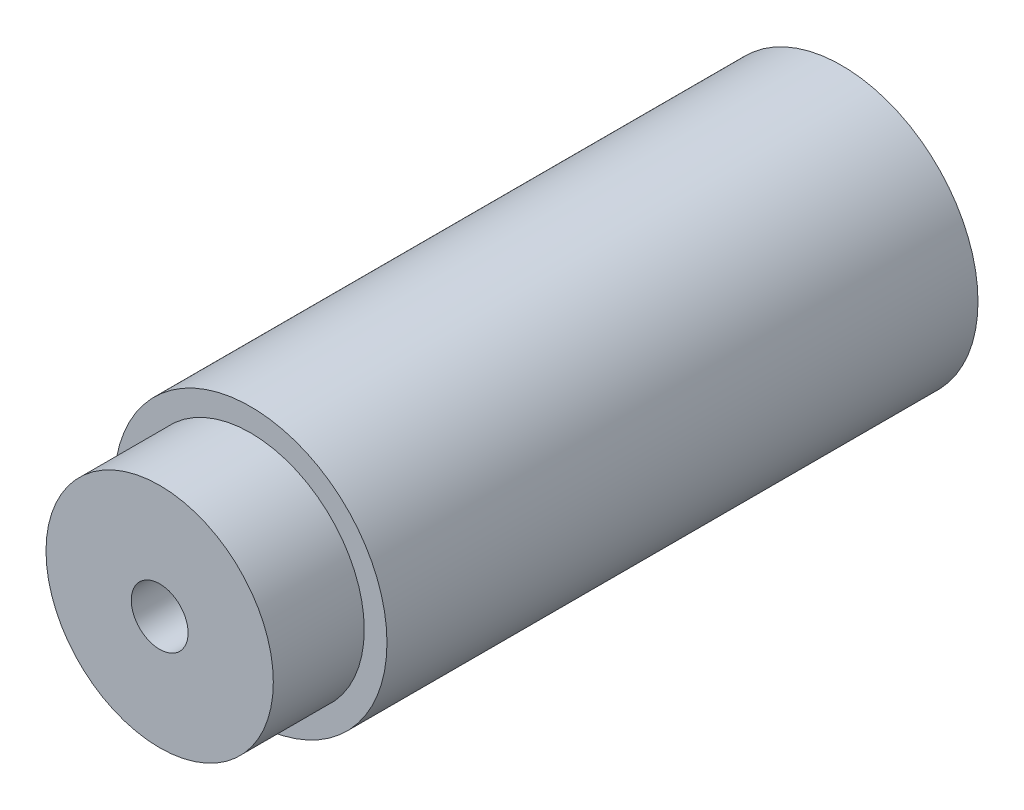
SolidWorks part; units mm, degrees
ref_plane "正面" through (0, 0, 0) normal (0, 0, 1) x (1, 0, 0)
ref_plane "平面" through (0, 0, 0) normal (0, 1, 0) x (1, 0, 0)
ref_plane "右側面" through (0, 0, 0) normal (1, 0, 0) x (0, 0, -1)
sketch "ｽｹｯﾁ1" plane through (0, 0, 0) normal (0, 0, 1) x (1, 0, 0)
  circle A0 centre (0, 0) radius 6
  dimension "D1" = 12
extrude "ﾎﾞｽ - 押し出し1" add sketch "ｽｹｯﾁ1" along normal blind 30
sketch "ｽｹｯﾁ2" plane through (0, 0, 30) normal (0, 0, 1) x (1, 0, 0)
  circle A0 centre (0, 0) radius 6
  circle A1 centre (0, 0) radius 5
  circle A2 centre (0, 0) radius 6 construction
  dimension "D1" = 10
extrude "ｶｯﾄ - 押し出し1" cut sketch "ｽｹｯﾁ2" against normal blind 4
ref_plane "平面1" through (0, 0, 15) normal (0, 0, 1) x (1, 0, 0)
sketch "ｽｹｯﾁ3" plane through (0, 0, 30) normal (0, 0, 1) x (1, 0, 0)
  circle A0 centre (0, 0) radius 1.25
  dimension "D1" = 2.5
extrude "ｶｯﾄ - 押し出し2" cut sketch "ｽｹｯﾁ3" against normal blind 10
